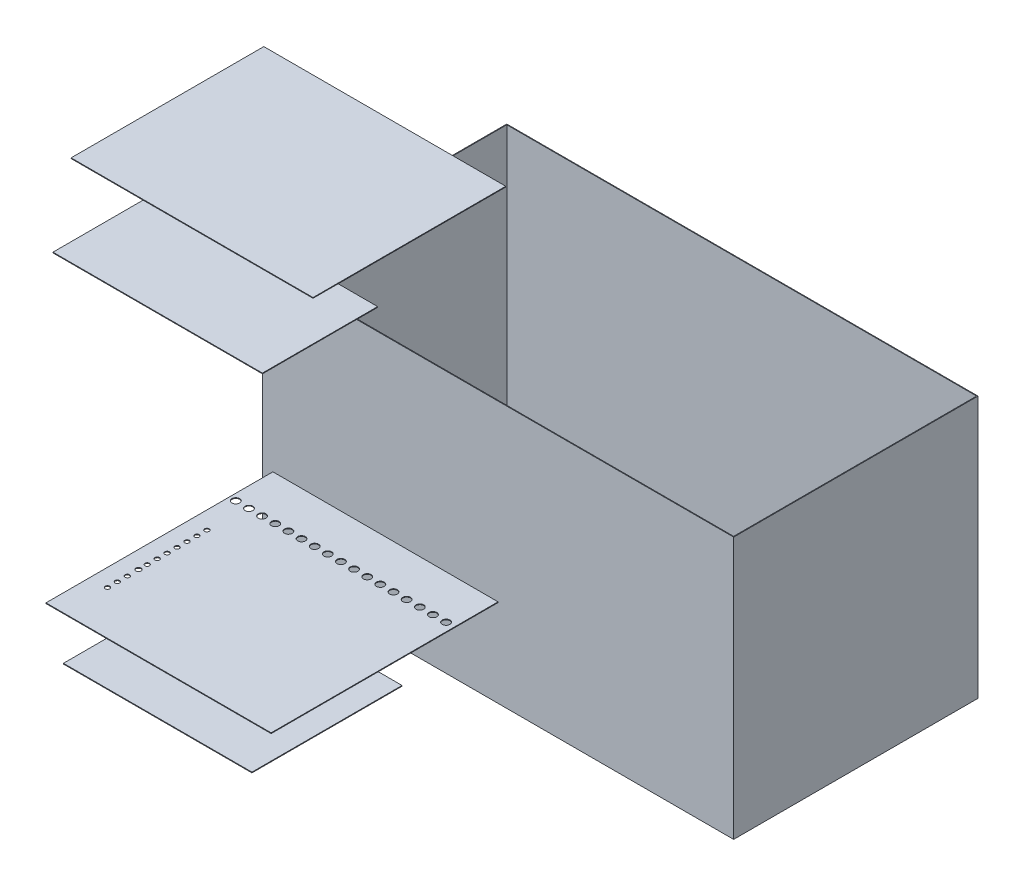
SolidWorks part; units mm, degrees
ref_plane "Спереди" through (0, 0, 0) normal (0, 0, 1) x (1, 0, 0)
ref_plane "Сверху" through (0, 0, 0) normal (0, 1, 0) x (1, 0, 0)
ref_plane "Справа" through (0, 0, 0) normal (1, 0, 0) x (0, 0, -1)
sketch "MASTER_FOOTPRINT" plane through (0, 0, 0) normal (0, 1, 0) x (1, 0, 0)
  line L1 (0, 0) -> (1350, 0)
  line L2 (0, 0) -> (0, 700)
  line L3 (0, 700) -> (1350, 700)
  line L4 (1350, 0) -> (1350, 700)
  dimension "D1" = 1350
  dimension "D2" = 700
extrude "BATH_BASE_PLATE" add sketch "MASTER_FOOTPRINT" along normal blind 750
shell "BATH_SHELL_2MM" thickness 2
sketch "Эскиз1" plane through (0, 0, 0) normal (0, 1, 0) x (1, 0, 0)
  line L1 (80, -220) -> (620, -220)
  line L2 (80, -220) -> (80, -650)
  line L3 (80, -650) -> (620, -650)
  line L4 (620, -220) -> (620, -650)
extrude "INLET_IMPACT_BAFFLE" add sketch "Эскиз1" along normal blind 2 from offset 125 separate body
sketch "Эскиз2" plane through (0, 0, 0) normal (0, 1, 0) x (1, 0, 0)
  line L0 (2, 2) -> (1348, 2) construction
  line L1 (30, 2) -> (675, 2)
  line L2 (30, 2) -> (30, -650)
  line L3 (30, -650) -> (675, -650)
  line L4 (675, 2) -> (675, -650)
  line L5 (80, -220) -> (80, -650) construction
  circle A0 centre (48.8235, -125) radius 11
  circle A1 centre (86.4706, -125) radius 11
  circle A2 centre (80, -239) radius 6.4706
  circle A3 centre (80, -267.5) radius 6.4706
  circle A4 centre (80, -296) radius 6.4706
  circle A5 centre (80, -324.5) radius 6.4706
  circle A6 centre (80, -353) radius 6.4706
  circle A7 centre (80, -381.5) radius 6.4706
  circle A8 centre (80, -410) radius 6.4706
  circle A9 centre (80, -435) radius 7.3565
  circle A10 centre (80, -467) radius 6.4706
  circle A11 centre (80, -495.5) radius 6.4706
  circle A12 centre (80, -524) radius 6.4706
  circle A13 centre (124.1176, -125) radius 11
  circle A14 centre (161.7647, -125) radius 11
  circle A15 centre (199.4118, -125) radius 11
  circle A16 centre (237.0588, -125) radius 11
  circle A17 centre (274.7059, -125) radius 11
  circle A18 centre (312.3529, -125) radius 11
  circle A19 centre (350, -125) radius 11
  circle A20 centre (387.6471, -125) radius 11
  circle A21 centre (425.2941, -125) radius 11
  circle A22 centre (462.9412, -125) radius 11
  circle A23 centre (500.5882, -125) radius 11
  circle A24 centre (538.2353, -125) radius 11
  circle A25 centre (575.8824, -125) radius 11
  circle A26 centre (613.5294, -125) radius 11
  circle A27 centre (651.1765, -125) radius 11
extrude "DISTRIBUTOR_D22" add sketch "Эскиз2" along normal blind 2 from offset 250 separate body
sketch "Эскиз3" plane through (0, 0, 0) normal (0, 1, 0) x (1, 0, 0)
  line L0 (30, -650) -> (675, -650) construction
  line L1 (50, -320) -> (650, -320)
  line L2 (50, -320) -> (50, -650)
  line L3 (50, -650) -> (650, -650)
  line L4 (650, -320) -> (650, -650)
extrude "OUTLET_SUBMERGED_BAFFLE" add sketch "Эскиз3" along normal blind 2 from offset 1130 separate body
sketch "Эскиз4" plane through (0, 0, 0) normal (0, 1, 0) x (1, 0, 0)
  line L1 (2, 2) -> (695, 2)
  line L2 (2, 2) -> (2, -550)
  line L3 (2, -550) -> (695, -550)
  line L4 (695, 2) -> (695, -550)
extrude "OVERFLOW_WEIR_Z550" add sketch "Эскиз4" along normal blind 2 from offset 1290 separate body
equation "\"AI_Q_Peak\"= 0.006"
equation "\"AI_B_Bath\"= 700"
equation "\"AI_L_Settle\"= 900"
equation "\"AI_L_Inlet\"= 250"
equation "\"AI_L_Outlet\"= 200"
equation "\"AI_L_Bath\"= 1350"
equation "\"AI_H_Water\"= 550"
equation "\"AI_H_Freeboard\"= 200"
equation "\"AI_H_Bath\"= 750"
equation "\"AI_Shell_Thickness\"= 2"
equation "\"AI_Inlet_DN\"= 100"
equation "\"AI_Weir_Width\"= 600"
equation "\"AI_Inlet_Baffle_Offset\"= 125"
equation "\"AI_Distributor_Open_Area\"= 0.28"
equation "\"AI_Distributor_Hole_Dia\"= 22"
equation "\"AI_Distributor_Blind_Zone\"= 110"
equation "\"AI_Outlet_Baffle_Depth\"= 250"
equation "\"AI_Screw_Diameter\"= 100"
equation "\"AI_Screw_Pitch\"= 100"
equation "\"AI_Screw_Angle\"= 30"
equation "\"AI_Screw_Rpm\"= 15"
equation "\"AI_Screw_Clearance\"= 5"
equation "\"AI_Liner_Thickness\"= 5"
equation "\"AI_Discharge_Height\"= 650"
equation "\"AI_Frame_Height\"= 500"
equation "\"D1@MASTER_FOOTPRINT\" = \"AI_L_Bath\""
equation "\"D2@MASTER_FOOTPRINT\" = \"AI_B_Bath\""
equation "\"D1@BATH_BASE_PLATE\" = \"AI_H_Bath\""
